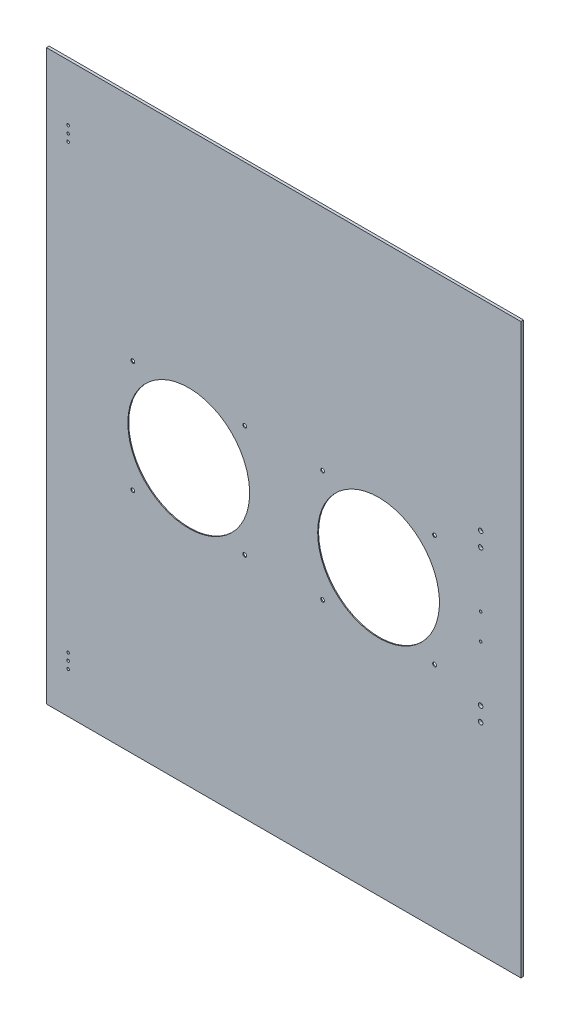
SolidWorks part; units mm, degrees
material "Acrylic (Medium-high impact)"
ref_plane "Front Plane" through (0, 0, 0) normal (0, 0, 1) x (1, 0, 0)
ref_plane "Top Plane" through (0, 0, 0) normal (0, 1, 0) x (1, 0, 0)
ref_plane "Right Plane" through (0, 0, 0) normal (1, 0, 0) x (0, 0, -1)
sketch "Sketch1" plane through (0, 0, 0) normal (0, 0, 1) x (1, 0, 0)
  line L1 (-476.5049, 294.7573) -> (53.4951, 294.7573)
  line L2 (-476.5049, 294.7573) -> (-476.5049, -340.2427)
  line L3 (-476.5049, -340.2427) -> (53.4951, -340.2427)
  line L4 (53.4951, 294.7573) -> (53.4951, -340.2427)
  dimension "D1" = 635
  dimension "D2" = 530
extrude "Boss-Extrude1" add sketch "Sketch1" along normal blind 3
sketch "Sketch2" plane through (0, 0, 3) normal (0, 0, 1) x (1, 0, 0)
  line L0 (-476.5049, 294.7573) -> (-476.5049, -340.2427) construction
  line L1 (53.4951, 294.7573) -> (-476.5049, 294.7573) construction
  line L2 (-476.5049, -340.2427) -> (53.4951, -340.2427) construction
  circle A0 centre (-452.2449, 231.7573) radius 1.5
  circle A1 centre (-452.2449, 223.7573) radius 1.5
  circle A2 centre (-452.2449, 215.7573) radius 1.5
  circle A3 centre (-452.2449, -278.2427) radius 1.5
  circle A4 centre (-452.2449, -286.2427) radius 1.5
  circle A5 centre (-452.2449, -294.2427) radius 1.5
  dimension "D1" = 3
  dimension "D4" = 8
  dimension "D5" = 24.26
  dimension "D6" = 8
  dimension "D7" = 24.26
  dimension "D8" = 3
  dimension "D11" = 46
  dimension "D12" = 24.26
  dimension "D2" = 24.26
  dimension "D3" = 63
  dimension "D9" = 8
  dimension "D10" = 8
extrude "Cut-Extrude1" cut sketch "Sketch2" against normal through all
sketch "Sketch3" plane through (0, 0, 3) normal (0, 0, 1) x (1, 0, 0)
  line L0 (-476.5049, -22.7427) -> (53.4951, -22.7427) construction
  line L1 (-476.5049, 294.7573) -> (-476.5049, -340.2427) construction
  line L2 (53.4951, -340.2427) -> (53.4951, 294.7573) construction
  line L3 (8.4951, 294.7573) -> (8.4951, -340.2427) construction
  line L4 (53.4951, 294.7573) -> (-476.5049, 294.7573) construction
  line L5 (-476.5049, -340.2427) -> (53.4951, -340.2427) construction
  circle A0 centre (8.4951, 69.7573) radius 2.5
  circle A1 centre (8.4951, 53.7573) radius 2.5
  circle A2 centre (8.4951, -99.2427) radius 2.5
  circle A3 centre (8.4951, -115.2427) radius 2.5
  circle A4 centre (8.4951, -8.2427) radius 1.5
  circle A5 centre (8.4951, -37.2427) radius 1.5
  dimension "D1" = 5
  dimension "D2" = 5
  dimension "D3" = 16
  dimension "D4" = 5
  dimension "D5" = 5
  dimension "D6" = 16
  dimension "D7" = 185
  dimension "D8" = 92.5
  dimension "D9" = 45
  dimension "D10" = 45
  dimension "D11" = 45
  dimension "D12" = 45
  dimension "D13" = 3
  dimension "D14" = 3
  dimension "D15" = 29
  dimension "D16" = 14.5
extrude "Cut-Extrude2" cut sketch "Sketch3" against normal through all
sketch "Sketch13" plane through (0, 0, 0) normal (0, 0, -1) x (-1, 0, 0)
  line L0 (211.5049, 294.7573) -> (211.5049, -340.2427) construction
  line L1 (-53.4951, 294.7573) -> (476.5049, 294.7573) construction
  line L2 (476.5049, -340.2427) -> (-53.4951, -340.2427) construction
  line L3 (-53.4951, -22.7427) -> (476.5049, -22.7427) construction
  line L4 (-53.4951, -340.2427) -> (-53.4951, 294.7573) construction
  line L5 (476.5049, 294.7573) -> (476.5049, -340.2427) construction
  line L7 (35.0049, 47.7573) -> (176.0049, 47.7573)
  line L8 (35.0049, 47.7573) -> (35.0049, -93.2427)
  line L9 (35.0049, -93.2427) -> (176.0049, -93.2427)
  line L10 (176.0049, 47.7573) -> (176.0049, -93.2427)
  line L11 (247.0049, 47.7573) -> (388.0049, 47.7573)
  line L12 (247.0049, 47.7573) -> (247.0049, -93.2427)
  line L13 (247.0049, -93.2427) -> (388.0049, -93.2427)
  line L14 (388.0049, 47.7573) -> (388.0049, -93.2427)
  dimension "D1" = 141
  dimension "D2" = 141
  dimension "D3" = 70.5
  dimension "D4" = 35.5
  dimension "D5" = 35.5
  dimension "D6" = 141
  dimension "D7" = 70.5
  dimension "D8" = 141
extrude "Cut-Extrude20" cut sketch "Sketch13" against normal blind 2 contours L8 L7 L10 L9 | L12 L11 L14 L13
sketch "Sketch14" plane through (0, 0, 2) normal (0, 0, -1) x (-1, 0, 0)
  line L0 (35.0049, 47.7573) -> (176.0049, 47.7573) construction
  line L1 (35.0049, 47.7573) -> (35.0049, -93.2427) construction
  line L2 (176.0049, 47.7573) -> (176.0049, -93.2427) construction
  line L3 (35.0049, -93.2427) -> (176.0049, -93.2427) construction
  line L4 (105.5049, 47.7573) -> (105.5049, -93.2427) construction
  line L5 (35.0049, 47.7573) -> (176.0049, 47.7573) construction
  line L6 (35.0049, -93.2427) -> (176.0049, -93.2427) construction
  line L7 (35.0049, -22.7427) -> (176.0049, -22.7427) construction
  line L8 (35.0049, 47.7573) -> (35.0049, -93.2427) construction
  circle A0 centre (43.0049, 39.7573) radius 2.085
  circle A1 centre (168.0049, 39.7573) radius 2.085
  circle A2 centre (43.0049, -85.2427) radius 2.085
  circle A3 centre (168.0049, -85.2427) radius 2.085
  circle A4 centre (105.5049, -22.7427) radius 68
  dimension "D1" = 8
  dimension "D2" = 8
  dimension "D3" = 8
  dimension "D4" = 8
  dimension "D5" = 8
  dimension "D6" = 8
  dimension "D7" = 8
  dimension "D8" = 8
  dimension "D9" = 136
extrude "Cut-Extrude21" cut sketch "Sketch14" against normal through all
sketch "Sketch15" plane through (0, 0, 2) normal (0, 0, -1) x (-1, 0, 0)
  line L0 (247.0049, 47.7573) -> (247.0049, -93.2427) construction
  line L1 (247.0049, -93.2427) -> (388.0049, -93.2427) construction
  line L2 (388.0049, 47.7573) -> (388.0049, -93.2427) construction
  line L3 (247.0049, 47.7573) -> (388.0049, 47.7573) construction
  line L4 (317.5049, 47.7573) -> (317.5049, -93.3702) construction
  line L5 (247.0049, -22.7427) -> (389.0008, -22.7427) construction
  circle A0 centre (255.0049, 39.7573) radius 2.085
  circle A1 centre (380.0049, 39.7573) radius 2.085
  circle A2 centre (255.0049, -85.2427) radius 2.085
  circle A3 centre (380.0049, -85.2427) radius 2.085
  circle A4 centre (317.5049, -22.8065) radius 68
  dimension "D1" = 8
  dimension "D2" = 8
  dimension "D3" = 8
  dimension "D4" = 8
  dimension "D6" = 8
  dimension "D7" = 8
  dimension "D9" = 136
  dimension "D5" = 8
  dimension "D8" = 8
extrude "Cut-Extrude22" cut sketch "Sketch15" against normal through all
